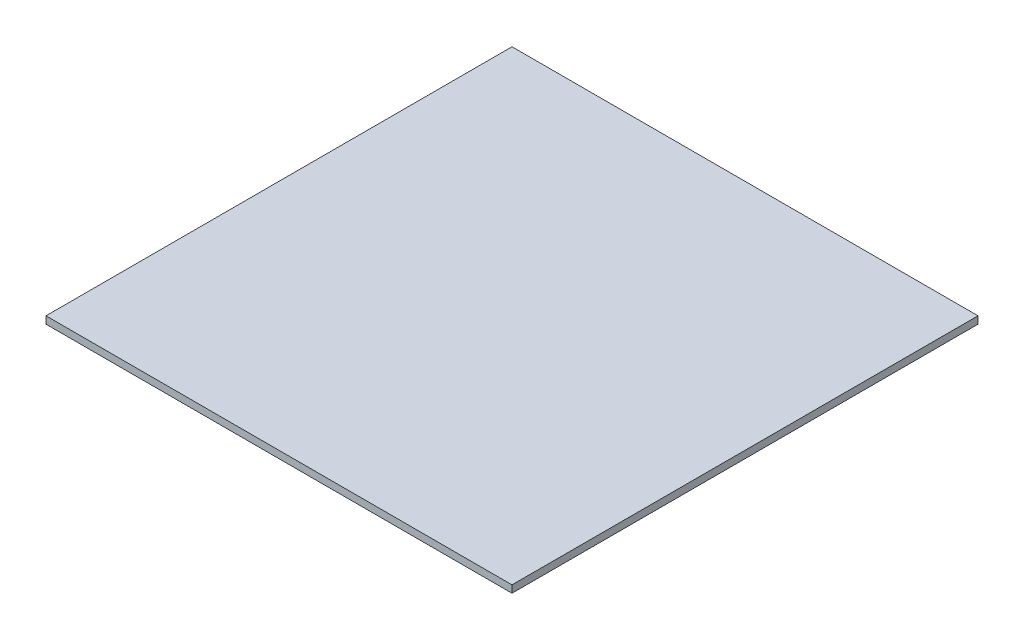
SolidWorks part; units mm, degrees
material "Maple"
ref_plane "Front Plane" through (0, 0, 0) normal (0, 0, 1) x (1, 0, 0)
ref_plane "Top Plane" through (0, 0, 0) normal (0, 1, 0) x (1, 0, 0)
ref_plane "Right Plane" through (0, 0, 0) normal (1, 0, 0) x (0, 0, -1)
sketch "Sketch1" plane through (0, 0, 0) normal (0, 1, 0) x (1, 0, 0)
  line L1 (-152.4, -152.4) -> (152.4, -152.4)
  line L2 (-152.4, -152.4) -> (-152.4, 152.4)
  line L3 (-152.4, 152.4) -> (152.4, 152.4)
  line L4 (152.4, -152.4) -> (152.4, 152.4)
  line L5 (-152.4, -152.4) -> (152.4, 152.4) construction
  line L6 (-152.4, 152.4) -> (152.4, -152.4) construction
  point P0 (0, 0)
  dimension "D1" = 304.8
  dimension "D2" = 304.8
extrude "Boss-Extrude1" add sketch "Sketch1" along normal mid plane 4.7625 contours L3 L4 L1 L2
sketch "Sketch2" [suppressed] plane through (0, 2.3813, 0) normal (0, 1, 0) x (1, 0, 0)
  line L0 (-279.4, -152.4) -> (-279.4, 152.4) construction
  line L1 (-279.4, 133.35) -> (-247.65, 133.35)
  line L2 (-279.4, 133.35) -> (-279.4, -133.35)
  line L3 (-279.4, -133.35) -> (-247.65, -133.35)
  line L4 (-247.65, 133.35) -> (-247.65, -133.35)
  line L5 (279.4, -152.4) -> (279.4, 152.4) construction
  line L6 (279.4, 133.35) -> (247.65, 133.35)
  line L7 (279.4, 133.35) -> (279.4, -133.35)
  line L8 (279.4, -133.35) -> (247.65, -133.35)
  line L9 (247.65, 133.35) -> (247.65, -133.35)
  line L10 (-247.65, 0) -> (247.65, 0) construction
  line L11 (-279.4, -152.4) -> (279.4, -152.4) construction
  dimension "D1" = 38.1
  dimension "D2" = 19.05
extrude "Cut-Extrude1" [suppressed] cut sketch "Sketch2" against normal through all
sketch "Sketch3" [suppressed] plane through (0, 2.3813, 0) normal (0, 1, 0) x (1, 0, 0)
  line L0 (-279.4, 152.4) -> (279.4, 152.4) construction
  line L1 (-196.85, 152.4) -> (196.85, 152.4)
  line L2 (-196.85, 152.4) -> (-196.85, 127)
  line L3 (-196.85, 127) -> (196.85, 127)
  line L4 (196.85, 152.4) -> (196.85, 127)
  line L5 (0, 0) -> (0, 127) construction
  line L6 (-247.65, -133.35) -> (-247.65, 133.35) construction
  dimension "D1" = 50.8
  dimension "D2" = 25.4
extrude "Cut-Extrude2" [suppressed] cut sketch "Sketch3" against normal through all
sketch "Sketch4" [suppressed] plane through (0, 2.3813, 0) normal (0, 1, 0) x (1, 0, 0)
  line L0 (-200.025, 123.825) -> (200.025, 123.825) construction
  line L1 (-200.025, 133.35) -> (200.025, 133.35)
  line L2 (-200.025, 114.3) -> (200.025, 114.3)
  line L3 (-279.4, -152.4) -> (279.4, -152.4) construction
  line L4 (-279.4, 152.4) -> (-234.95, 152.4)
  line L5 (-279.4, 152.4) -> (-279.4, -152.4)
  line L7 (0, 123.825) -> (0, 0) construction
  line L8 (-279.4, 152.4) -> (279.4, 152.4) construction
  line L9 (-279.4, -152.4) -> (-234.95, -152.4)
  line L10 (-234.95, 152.4) -> (-234.95, -152.4)
  line L12 (279.4, 152.4) -> (234.95, 152.4)
  line L13 (279.4, 152.4) -> (279.4, -152.4)
  line L14 (279.4, -152.4) -> (234.95, -152.4)
  line L15 (234.95, 152.4) -> (234.95, -152.4)
  arc A0 (-200.025, 133.35) -> (-200.025, 114.3) centre (-200.025, 123.825) ccw
  arc A1 (200.025, 114.3) -> (200.025, 133.35) centre (200.025, 123.825) ccw
  point P2 (0, 123.825)
  dimension "D1" = 25.4
  dimension "D2" = 19.05
  dimension "D3" = 19.05
  dimension "D4" = 44.45
extrude "Cut-Extrude3" [suppressed] cut sketch "Sketch4" against normal through all
sketch "Sketch5" [suppressed] plane through (0, 2.3813, 0) normal (0, 1, 0) x (1, 0, 0)
  line L0 (-234.95, 152.4) -> (-234.95, -152.4)
  line L1 (-279.4, 152.4) -> (279.4, 152.4) construction
  line L2 (-279.4, -152.4) -> (279.4, -152.4) construction
  line L3 (-279.4, -152.4) -> (-279.4, -133.35) construction
  dimension "D1" = 44.45
extrude "Cut-Extrude4" [suppressed] cut sketch "Sketch5" against normal through all and the other way through all
sketch "Sketch6" [suppressed] plane through (0, 2.3813, 0) normal (0, 1, 0) x (1, 0, 0)
  line L0 (-200.025, 123.825) -> (200.025, 123.825) construction
  line L1 (-200.025, 133.35) -> (200.025, 133.35)
  line L2 (-200.025, 114.3) -> (200.025, 114.3)
  line L3 (-298.45, 152.4) -> (298.45, 152.4) construction
  line L4 (298.45, -152.4) -> (298.45, 152.4) construction
  arc A0 (-200.025, 133.35) -> (-200.025, 114.3) centre (-200.025, 123.825) ccw
  arc A1 (200.025, 114.3) -> (200.025, 133.35) centre (200.025, 123.825) ccw
  point P2 (0, 123.825)
  dimension "D1" = 19.05
  dimension "D2" = 19.05
  dimension "D3" = 88.9
extrude "Cut-Extrude5" [suppressed] cut sketch "Sketch6" against normal through all
sketch "Sketch7" [suppressed] plane through (0, 2.3813, 0) normal (0, 1, 0) x (1, 0, 0)
  line L1 (-234.95, -44.45) -> (234.95, -44.45)
  line L2 (-234.95, -44.45) -> (-234.95, 44.45)
  line L3 (-234.95, 44.45) -> (234.95, 44.45)
  line L4 (234.95, -44.45) -> (234.95, 44.45)
  line L5 (-234.95, -44.45) -> (234.95, 44.45) construction
  line L6 (-234.95, 44.45) -> (234.95, -44.45) construction
  point P0 (0, 0)
  dimension "D1" = 88.9
  dimension "D2" = 469.9
extrude "Cut-Extrude6" [suppressed] cut sketch "Sketch7" against normal through all
sketch "Sketch8" [suppressed] plane through (0, 2.3813, 0) normal (0, 1, 0) x (1, 0, 0)
  line L0 (-15.875, 123.825) -> (15.875, 123.825) construction
  line L1 (-15.875, 133.35) -> (15.875, 133.35)
  line L2 (-15.875, 114.3) -> (15.875, 114.3)
  line L3 (0, 123.825) -> (0, 0) construction
  line L4 (-298.45, 152.4) -> (298.45, 152.4) construction
  arc A0 (-15.875, 133.35) -> (-15.875, 114.3) centre (-15.875, 123.825) ccw
  arc A1 (15.875, 114.3) -> (15.875, 133.35) centre (15.875, 123.825) ccw
  point P2 (0, 123.825)
  dimension "D2" = 50.8
  dimension "D1" = 19.05
  dimension "D3" = 19.05
extrude "Cut-Extrude7" [suppressed] cut sketch "Sketch8" against normal through all
